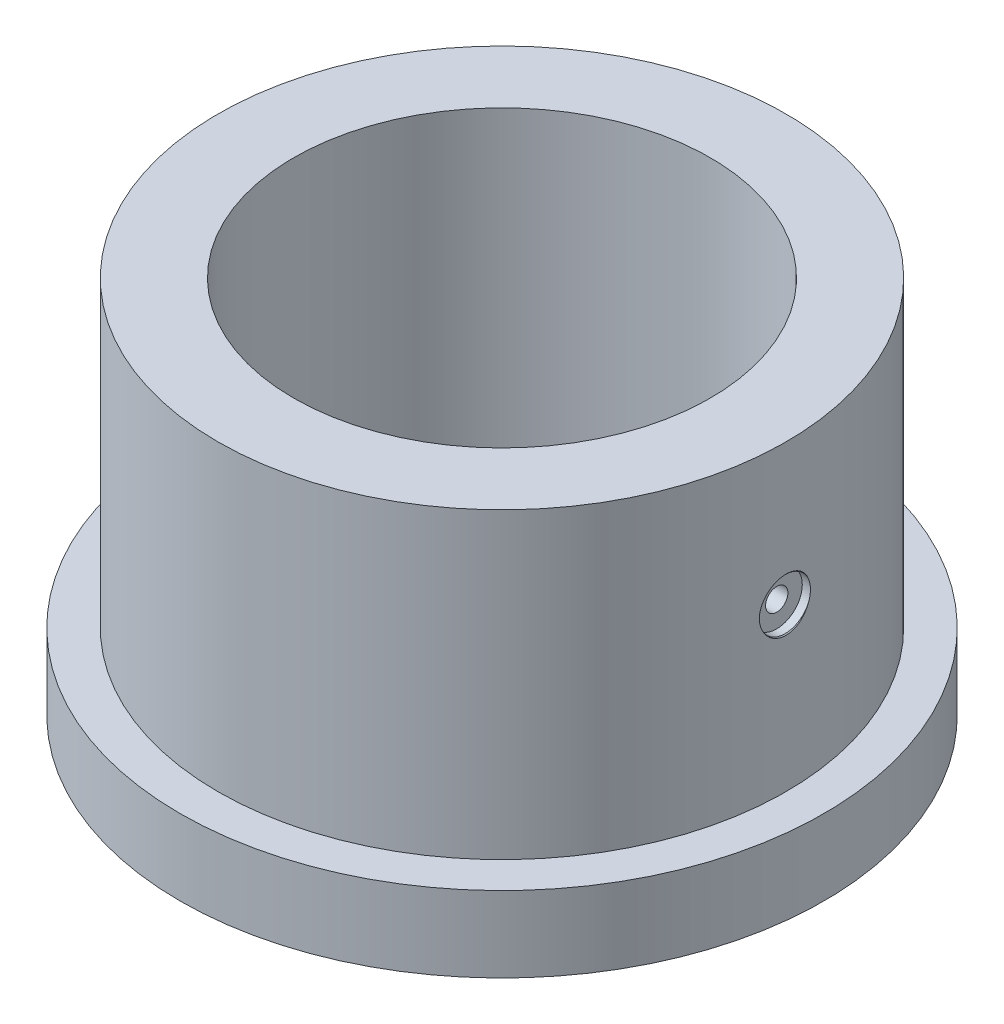
SolidWorks part; units mm, degrees
ref_plane "Front Plane" through (0, 0, 0) normal (0, 0, 1) x (1, 0, 0)
ref_plane "Top Plane" through (0, 0, 0) normal (0, 1, 0) x (1, 0, 0)
ref_plane "Right Plane" through (0, 0, 0) normal (1, 0, 0) x (0, 0, -1)
sketch "Sketch1" plane through (0, 0, 0) normal (0, 1, 0) x (1, 0, 0)
  circle A1 centre (0, 0) radius 37.5
  dimension "D2" = 75
extrude "Boss-Extrude1" add sketch "Sketch1" along normal blind 40 contours A1
sketch "Sketch2" plane through (0, 0, 0) normal (0, 1, 0) x (1, 0, 0)
  circle A0 centre (0, 0) radius 42.5
  dimension "D1" = 85
extrude "Boss-Extrude2" add sketch "Sketch2" against normal blind 10
sketch "Sketch3" plane through (0, 0, 0) normal (0, 1, 0) x (1, 0, 0)
  circle A0 centre (0, 0) radius 27.5
  dimension "D1" = 55
extrude "Cut-Extrude1" cut sketch "Sketch3" along normal blind 40 and the other way blind 10
ref_plane "Plane1" through (38, 0, 0) normal (1, 0, 0) x (0, 0, -1)
sketch "Sketch7" plane through (38, 0, 0) normal (1, 0, 0) x (0, 0, -1)
  line L0 (0, 42.7654) -> (0, 0) construction
  line L1 (42.5, 0) -> (-42.5, 0) construction
  line L2 (0, 21.3827) -> (-37.5, 21.3827) construction
  line L3 (-37.5, 40) -> (-37.5, 0) construction
  point P9 (0, 21.3827)
hole_wizard "CBORE for #4 Binding Head Machine Screw1" positions "Sketch11" profile "Sketch12" counterbore size "#4" standard "ANSI Inch"
sketch "Sketch11" plane through (38, 0, 0) normal (1, 0, 0) x (0, 0, -1)
  point P0 (0, 21.3827)
sketch "Sketch12" plane through (38, 21.3827, 0) normal (0, 1, 0) x (0, 0, -1)
  line L0 (0, 0) -> (0, 18.8852)
  line L1 (0, 18.8852) -> (1.4732, 18)
  line L2 (1.4732, 18) -> (1.4732, 1.7272)
  line L3 (1.4732, 1.7272) -> (3.3731, 1.7272)
  line L5 (3.3731, 1.7272) -> (3.3731, 0.624)
  line L6 (3.3731, 0.624) -> (4.0081, 0)
  line L7 (4.0081, 0) -> (0, 0)
  line L8 (-3.3731, 0.624) -> (-4.0081, 0) construction
  line L10 (0, 18.8852) -> (-1.4732, 18) construction
  line L11 (0, -6.35) -> (0, 107.95) construction
  dimension "Hole Dia." = 2.9464
  dimension "Hole Depth" = 18
  dimension "C'Bore Dia." = 6.7462
  dimension "C'Bore Depth" = 1.7272
  dimension "Near C'Sink Dia." = 8.0162
  dimension "Near C'Sink Angle" = 91
  dimension "Drill Angle" = 118
